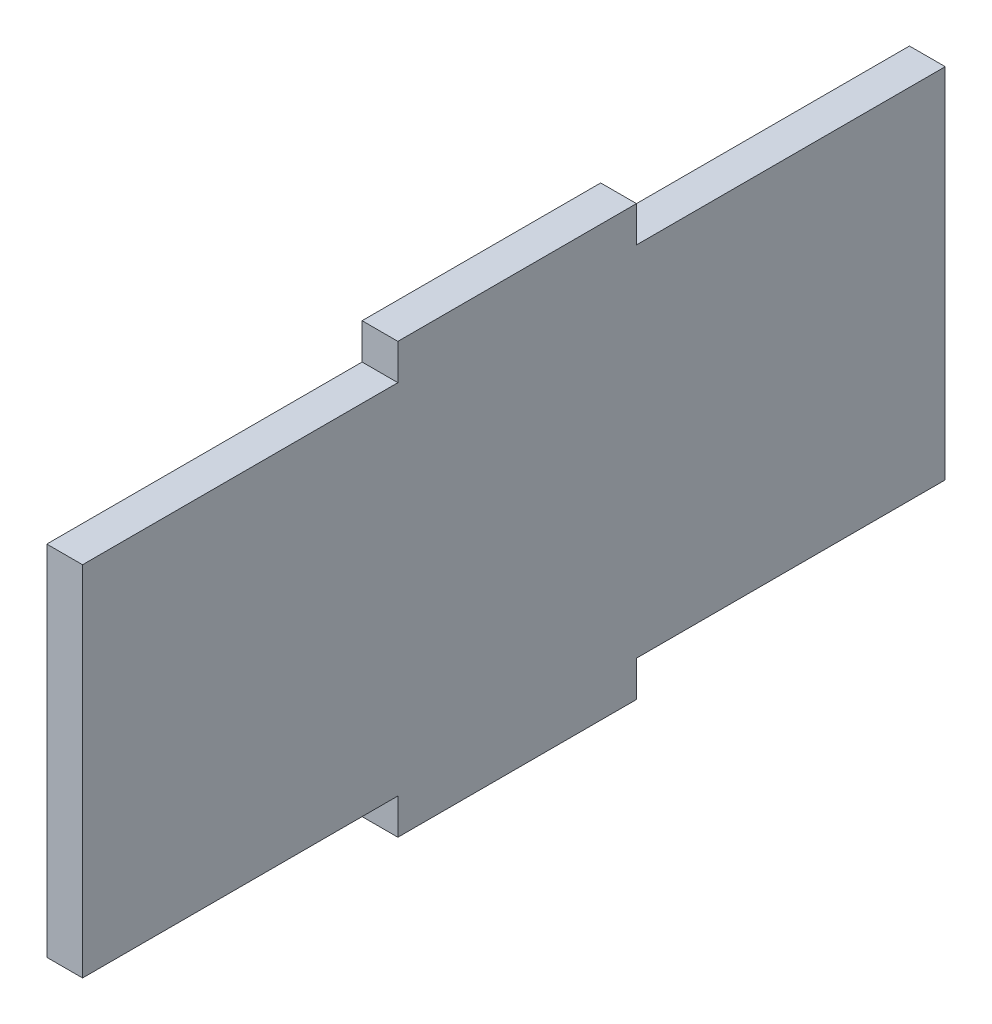
SolidWorks part; units mm, degrees
ref_plane "Front Plane" through (0, 0, 0) normal (0, 0, 1) x (1, 0, 0)
ref_plane "Top Plane" through (0, 0, 0) normal (0, 1, 0) x (1, 0, 0)
ref_plane "Right Plane" through (0, 0, 0) normal (1, 0, 0) x (0, 0, -1)
sketch "Sketch1" plane through (0, 0, 0) normal (0, 1, 0) x (1, 0, 0)
  line L1 (-6.3207, -34.3916) -> (-3.3207, -34.3916)
  line L2 (-6.3207, -34.3916) -> (-6.3207, -54.3916)
  line L3 (-6.3207, -54.3916) -> (-3.3207, -54.3916)
  line L4 (-3.3207, -34.3916) -> (-3.3207, -54.3916)
extrude "Boss-Extrude1" add sketch "Sketch1" along normal blind 3
sketch "Sketch2" plane through (0, 3, 0) normal (0, 1, 0) x (1, 0, 0)
  line L0 (-6.3207, -34.3916) -> (-6.3207, -54.3916) construction
  line L1 (-6.3207, -8.5119) -> (-3.3207, -8.5119)
  line L2 (-6.3207, -8.5119) -> (-6.3207, -80.8219)
  line L3 (-6.3207, -80.8219) -> (-3.3207, -80.8219)
  line L4 (-3.3207, -8.5119) -> (-3.3207, -80.8219)
  line L6 (-3.3207, -54.3916) -> (-3.3207, -34.3916) construction
  point P8 (-3.3207, -44.3916)
extrude "Boss-Extrude2" add sketch "Sketch2" along normal blind 30
sketch "Sketch3" plane through (0, 33, 0) normal (0, 1, 0) x (1, 0, 0)
  line L1 (-3.3207, -34.3916) -> (-6.3207, -34.3916)
  line L2 (-3.3207, -34.3916) -> (-3.3207, -54.3916)
  line L3 (-3.3207, -54.3916) -> (-6.3207, -54.3916)
  line L4 (-6.3207, -34.3916) -> (-6.3207, -54.3916)
extrude "Boss-Extrude3" add sketch "Sketch3" along normal blind 3
